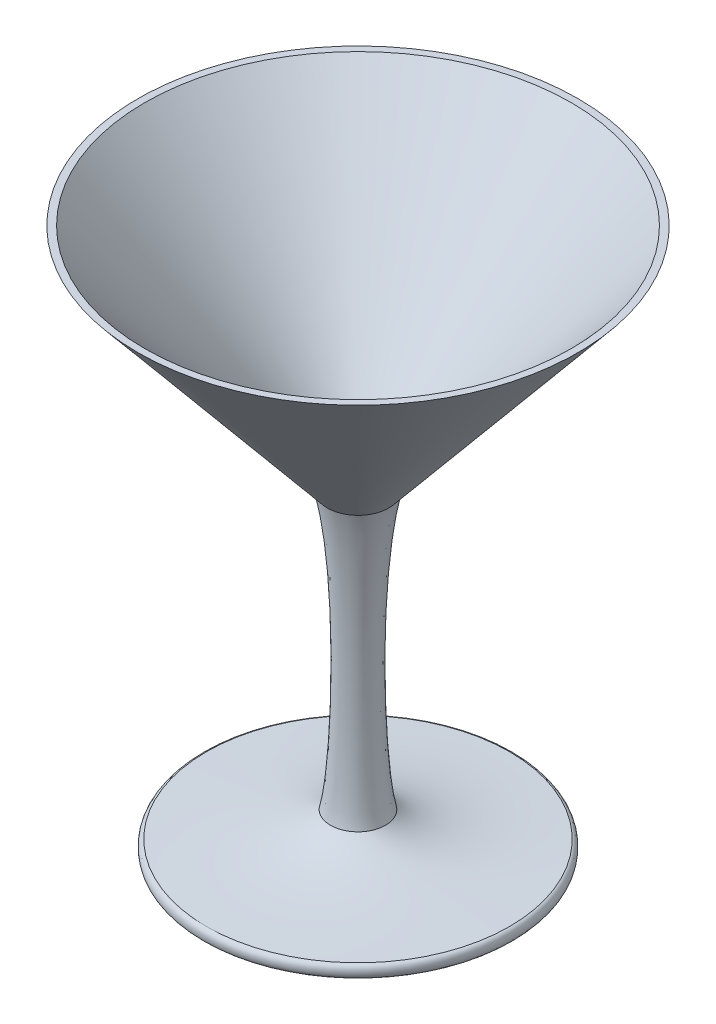
SolidWorks part; units mm, degrees
ref_plane "Płaszczyzna przednia" through (0, 0, 0) normal (0, 0, 1) x (1, 0, 0)
ref_plane "Płaszczyzna górna" through (0, 0, 0) normal (0, 1, 0) x (1, 0, 0)
ref_plane "Płaszczyzna prawa" through (0, 0, 0) normal (1, 0, 0) x (0, 0, -1)
sketch "Szkic1" plane through (0, 0, 0) normal (0, 0, 1) x (1, 0, 0)
  line L0 (-159.4207, -336.8775) -> (-191.0882, -336.8775)
  line L2 (-165.8103, -271.4046) -> (-205.2381, -223.6719)
  line L3 (-203.8069, -223.6719) -> (-164.1921, -268.4112)
  line L5 (-205.2381, -223.6719) -> (-203.8069, -223.6719)
  line L6 (-159.4207, -270.2448) -> (-159.4207, -336.8775)
  arc A0 (-164.1921, -268.4112) -> (-159.4207, -270.2448) centre (-159.4207, -263.1199) ccw
  spline S0 degree 3 poles (-165.8103, -271.4046) (-162.2046, -287.9303) (-163.2277, -321.7913) (-165.1441, -328.9533) knots 0 0 0 0 1 1 1 1
  spline S1 degree 3 poles (-165.1441, -328.9533) (-169.8375, -333.1718) (-179.5361, -333.8285) (-190.9646, -334.3043) knots 0 0 0 0 0.834301 0.834301 0.834301 0.834301
  spline S2 degree 3 poles (-190.9646, -334.3043) (-192.193, -334.6111) (-191.9255, -336.8828) (-191.0882, -336.8775) knots 0 0 0 0 0.195979 0.195979 0.195979 0.195979
revolve "Obrót1" add sketch "Szkic1" angle 360 about L6
